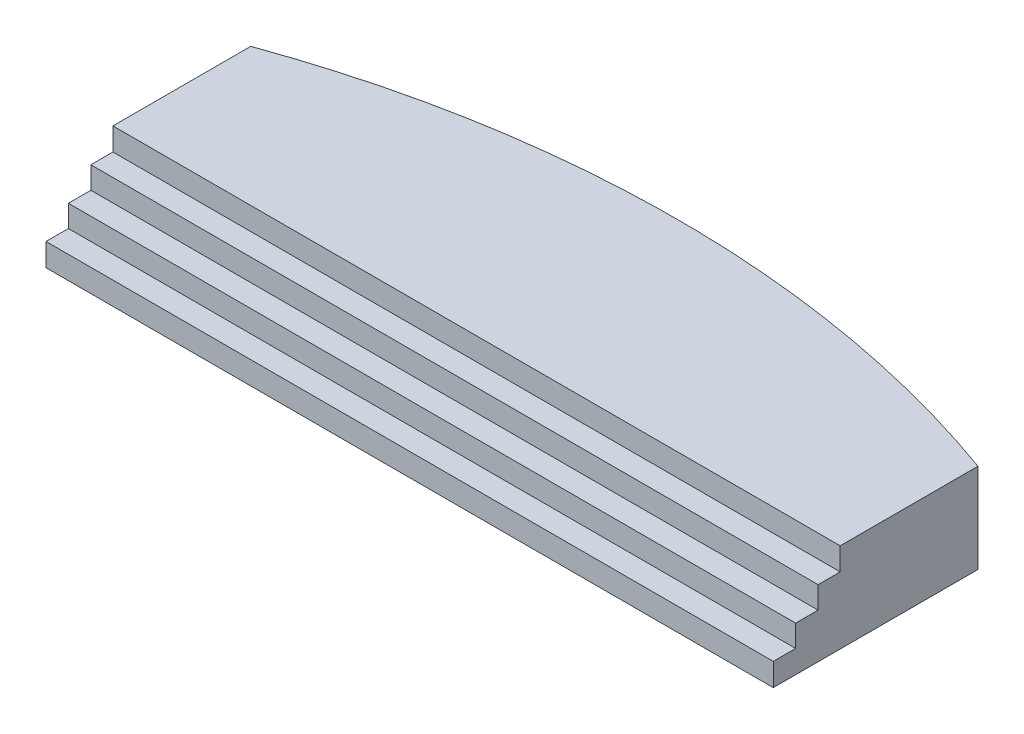
SolidWorks part; units mm, degrees
ref_plane "Front Plane" through (0, 0, 0) normal (0, 0, 1) x (1, 0, 0)
ref_plane "Top Plane" through (0, 0, 0) normal (0, 1, 0) x (1, 0, 0)
ref_plane "Right Plane" through (0, 0, 0) normal (1, 0, 0) x (0, 0, -1)
sketch "Sketch1" plane through (0, 0, 0) normal (0, 1, 0) x (1, 0, 0)
  line L0 (0, 12000) -> (0, 6000) construction
  line L1 (-4067.1162, 9000) -> (3864.1234, 9000)
  line L3 (-4067.1162, 9000) -> (-4067.1162, 11289.7549)
  line L4 (3864.1234, 9000) -> (3864.1234, 11360.8341)
  arc A1 (0, 12000) -> (-4067.1162, 11289.7549) centre (0, 0) ccw
  arc A2 (0, 12000) -> (3864.1234, 11360.8341) centre (0, 0) cw
extrude "Boss-Extrude1" add sketch "Sketch1" along normal blind 1000 contours A2 L4 L1 L3 A1
sketch "Sketch2" plane through (3864.1234, 0, 0) normal (1, 0, 0) x (0, 0, -1)
  line L1 (9000, 1000) -> (9000, 0) construction
  line L2 (9000, 254.9104) -> (9250.2457, 254.9104)
  line L3 (9250.2457, 254.9104) -> (9250.2457, 500)
  line L4 (9250.2457, 500) -> (9501.4119, 500)
  line L5 (9501.4119, 500) -> (9501.4119, 747.1151)
  line L6 (9501.4119, 747.1151) -> (9748.527, 747.1151)
  line L7 (9748.527, 747.1151) -> (9748.527, 1000)
  line L8 (9000, 1000) -> (11360.8341, 1000) construction
  line L9 (9748.527, 1000) -> (9000, 1000)
  line L10 (9000, 1000) -> (9000, 254.9104)
extrude "Cut-Extrude1" cut sketch "Sketch2" against normal blind 24000
sketch "Sketch3" plane through (0, 1000, 0) normal (0, 1, 0) x (1, 0, 0)
  line L0 (0, 9000) -> (0, 12000) construction
  line L1 (-4067.1162, 11289.7549) -> (3864.1234, 11289.7549)
  line L2 (-4067.1162, 11289.7549) -> (-4067.1162, 9000)
  line L3 (-4067.1162, 9000) -> (3864.1234, 9000)
  line L4 (3864.1234, 11289.7549) -> (3864.1234, 9000)
  line L5 (3864.1234, 11289.7549) -> (4067.1162, 11289.7549)
  line L6 (4067.1162, 11289.7549) -> (4067.1162, 9000)
  arc A1 (4067.1162, 11289.7549) -> (-4067.1162, 11289.7549) centre (0, 0) ccw
sketch "Sketch4" plane through (3864.1234, 0, 0) normal (1, 0, 0) x (0, 0, -1)
  line L0 (9000, 254.9104) -> (9000, 0)
  line L1 (9000, 0) -> (11360.8341, 0)
  line L2 (11360.8341, 0) -> (11360.8341, 1000)
  line L3 (11360.8341, 1000) -> (9748.527, 1000)
  line L4 (9748.527, 1000) -> (9748.527, 747.1151)
  line L5 (9748.527, 747.1151) -> (9501.4119, 747.1151)
  line L6 (9501.4119, 747.1151) -> (9501.4119, 500)
  line L7 (9501.4119, 500) -> (9250.2457, 500)
  line L8 (9250.2457, 500) -> (9250.2457, 254.9104)
  line L9 (9250.2457, 254.9104) -> (9000, 254.9104)
extrude "Boss-Extrude2" add sketch "Sketch4" along normal blind 202.9928
sketch "Sketch5" plane through (0, 1000, 0) normal (0, 1, 0) x (1, 0, 0)
  line L0 (4067.1162, 11289.7549) -> (4067.1162, 11360.8341)
  line L1 (4067.1162, 11360.8341) -> (3864.1234, 11360.8341)
  line L3 (0, 12000) -> (0, 9000) construction
  line L4 (-4067.1162, 9000) -> (4067.1162, 9000) construction
  line L5 (4067.1162, 11289.7549) -> (4067.1162, 9748.527)
  line L6 (4067.1162, 9748.527) -> (0, 9748.527)
  line L7 (-4067.1162, 9748.527) -> (4067.1162, 9748.527) construction
  arc A0 (3864.1234, 11360.8341) -> (-4067.1162, 11289.7549) centre (0, 0) ccw construction
  arc A1 (3864.1234, 11360.8341) -> (4067.1162, 11289.7549) centre (0, 0) cw
extrude "Cut-Extrude5" cut sketch "Sketch5" against normal blind 4000 contours L0 L1 A1
sketch "Sketch9" plane through (0, 0, 0) normal (0, -1, 0) x (1, 0, 0)
  line L0 (0, -9000) -> (0, -12000) construction
  line L1 (-4067.1162, -9000) -> (4067.1162, -9000) construction
  arc A0 (-4067.1162, -11289.7549) -> (4067.1162, -11289.7549) centre (0, 0) ccw construction
  dimension "D1" = 3000
